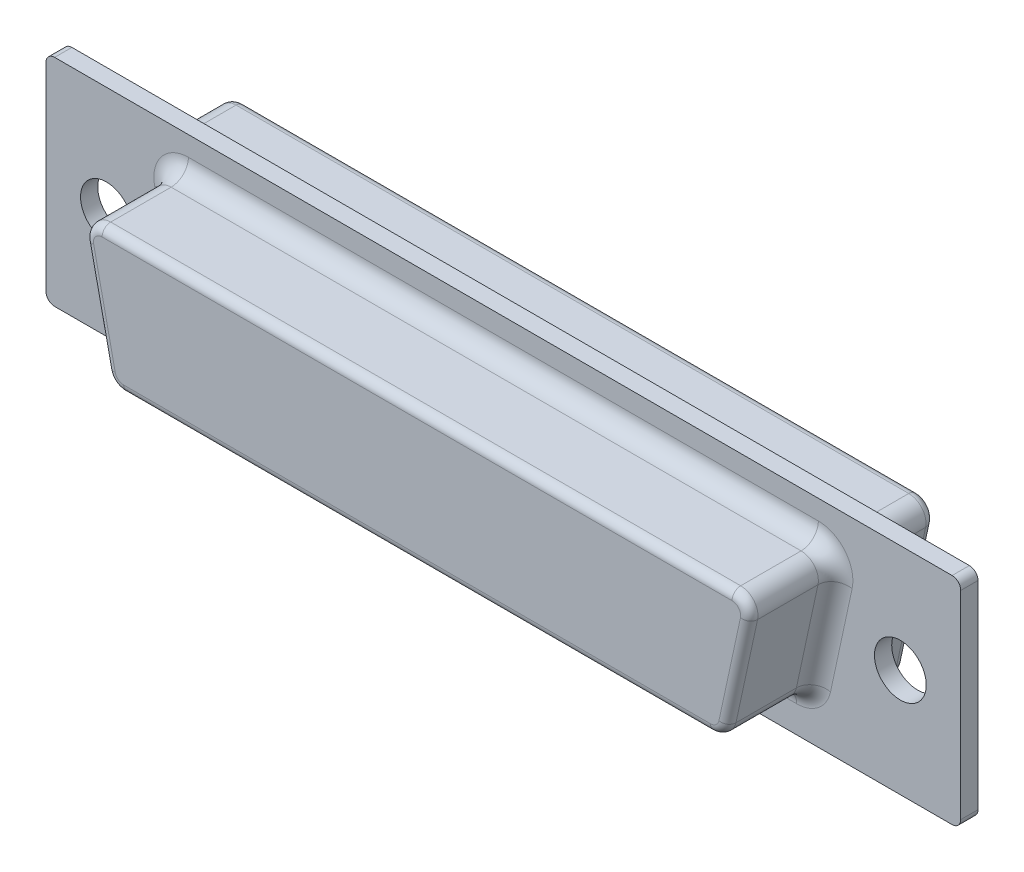
SolidWorks part; units mm, degrees
material "Plain Carbon Steel"
ref_plane "Front Plane" through (0, 0, 0) normal (0, 0, 1) x (1, 0, 0)
ref_plane "Top Plane" through (0, 0, 0) normal (0, 1, 0) x (1, 0, 0)
ref_plane "Right Plane" through (0, 0, 0) normal (1, 0, 0) x (0, 0, -1)
sketch "Sketch1" plane through (0, 0, 0) normal (0, 0, 1) x (1, 0, 0)
  line L1 (-26.5, -6.25) -> (26.5, -6.25)
  line L2 (-26.5, -6.25) -> (-26.5, 6.25)
  line L3 (-26.5, 6.25) -> (26.5, 6.25)
  line L4 (26.5, -6.25) -> (26.5, 6.25)
  line L5 (-26.5, -6.25) -> (26.5, 6.25) construction
  line L6 (-26.5, 6.25) -> (26.5, -6.25) construction
  point P0 (0, 0)
  dimension "D1" = 53
  dimension "D2" = 12.5
extrude "Boss-Extrude1" add sketch "Sketch1" along normal blind 1
sketch "Sketch2" plane through (0, 0, 1) normal (0, 0, 1) x (1, 0, 0)
  line L0 (0, 0) -> (0, 6.25) construction
  line L1 (26.5, 6.25) -> (-26.5, 6.25) construction
  line L2 (19.2276, 2.9) -> (17.9776, -2.9)
  line L3 (-19.2276, 2.9) -> (-17.9776, -2.9)
  line L4 (17, -3.6893) -> (-17, -3.6893)
  line L5 (18.25, 4.1107) -> (-18.25, 4.1107)
  line L6 (18.6026, 0) -> (-18.6026, 0) construction
  line L7 (-26.5, -6.25) -> (26.5, -6.25) construction
  arc A0 (17.9776, -2.9) -> (17, -3.6893) centre (17, -2.6893) cw
  arc A1 (19.2276, 2.9) -> (18.25, 4.1107) centre (18.25, 3.1107) ccw
  arc A2 (-17.9776, -2.9) -> (-17, -3.6893) centre (-17, -2.6893) ccw
  arc A3 (-19.2276, 2.9) -> (-18.25, 4.1107) centre (-18.25, 3.1107) cw
  point P9 (0, -3.6893)
  point P10 (0, 4.1107)
  point P13 (17.8074, -3.6893)
  point P16 (19.4885, 4.1107)
  point P19 (-17.8074, -3.6893)
  point P22 (-19.4885, 4.1107)
  dimension "D2" = 1
  dimension "D3" = 38.5
  dimension "D4" = 34
  dimension "D1" = 7.8
extrude "Boss-Extrude2" add sketch "Sketch2" along normal blind 5
sketch "Sketch3" plane through (0, 0, 1) normal (0, 0, 1) x (1, 0, 0)
  line L0 (-26.5, 0) -> (26.5, 0) construction
  line L1 (26.5, -6.25) -> (26.5, 6.25) construction
  line L2 (0, -6.25) -> (0, 6.25) construction
  line L3 (26.5, 6.25) -> (-26.5, 6.25) construction
  circle A0 centre (-23, 0) radius 1.5
  circle A1 centre (23, 0) radius 1.5
  point P6 (0, 0)
  point P14 (0, 0)
  dimension "D1" = 3
  dimension "D2" = 46
extrude "Cut-Extrude1" cut sketch "Sketch3" against normal through all
fillet "Fillet1" radius 1 8 edges at (19.028, 3.7389, 1) (18.6026, 0, 1) (17.6282, -3.4674, 1) (0, -3.6893, 1) (-17.6282, -3.4674, 1) (-18.6026, 0, 1) (-19.028, 3.7389, 1) (0, 4.1107, 1)
fillet "Fillet2" radius 0.5 12 edges at (19.028, 3.7389, 6) (18.6026, 0, 6) (17.6282, -3.4674, 6) (0, -3.6893, 6) (-17.6282, -3.4674, 6) (-18.6026, 0, 6) (-19.028, 3.7389, 6) (0, 4.1107, 6) (26.5, -6.25, 0.5) (-26.5, -6.25, 0.5) (-26.5, 6.25, 0.5) (26.5, 6.25, 0.5)
sketch "Sketch5" plane through (0, 0, 0) normal (0, 0, -1) x (-1, 0, 0)
  line L0 (19.2276, 2.9) -> (17.9776, -2.9) construction
  line L1 (17, -3.6893) -> (-17, -3.6893) construction
  line L2 (-17.9776, -2.9) -> (-19.2276, 2.9) construction
  line L3 (-18.25, 4.1107) -> (18.25, 4.1107) construction
  line L4 (19.4885, 4.1107) -> (17.8074, -3.6893) construction
  line L5 (17.8074, -3.6893) -> (-17.8074, -3.6893) construction
  line L6 (-17.8074, -3.6893) -> (-19.4885, 4.1107) construction
  line L7 (-19.4885, 4.1107) -> (19.4885, 4.1107) construction
  line L8 (-19.4885, 5.1107) -> (19.4885, 5.1107)
  line L9 (20.466, 3.9) -> (18.785, -3.9)
  line L10 (17.8074, -4.6893) -> (-17.8074, -4.6893)
  line L11 (-18.785, -3.9) -> (-20.466, 3.9)
  line L16 (18.6149, -4.6893) -> (-18.6149, -4.6893) construction
  line L17 (-18.6149, -4.6893) -> (-20.727, 5.1107) construction
  line L18 (20.727, 5.1107) -> (18.6149, -4.6893) construction
  line L19 (-20.727, 5.1107) -> (20.727, 5.1107) construction
  arc A0 (-17.8074, -4.6893) -> (-18.785, -3.9) centre (-17.8074, -3.6893) cw
  arc A1 (18.785, -3.9) -> (17.8074, -4.6893) centre (17.8074, -3.6893) cw
  arc A2 (19.4885, 5.1107) -> (20.466, 3.9) centre (19.4885, 4.1107) cw
  arc A3 (-19.4885, 5.1107) -> (-20.466, 3.9) centre (-19.4885, 4.1107) ccw
  dimension "D2" = 1
  dimension "D1" = 1
extrude "Boss-Extrude3" add sketch "Sketch5" along normal blind 3.5
fillet "Fillet3" radius 0.5 16 edges at (20.2665, 4.7389, 0) (0, 5.1107, 0) (-20.2665, 4.7389, 0) (-19.6255, 0, 0) (-18.4357, -4.4674, 0) (0, -4.6893, 0) (18.4357, -4.4674, 0) (19.6255, 0, 0) (20.2665, 4.7389, -3.5) (0, 5.1107, -3.5) (-20.2665, 4.7389, -3.5) (-19.6255, 0, -3.5) (-18.4357, -4.4674, -3.5) (0, -4.6893, -3.5) (18.4357, -4.4674, -3.5) (19.6255, 0, -3.5)
